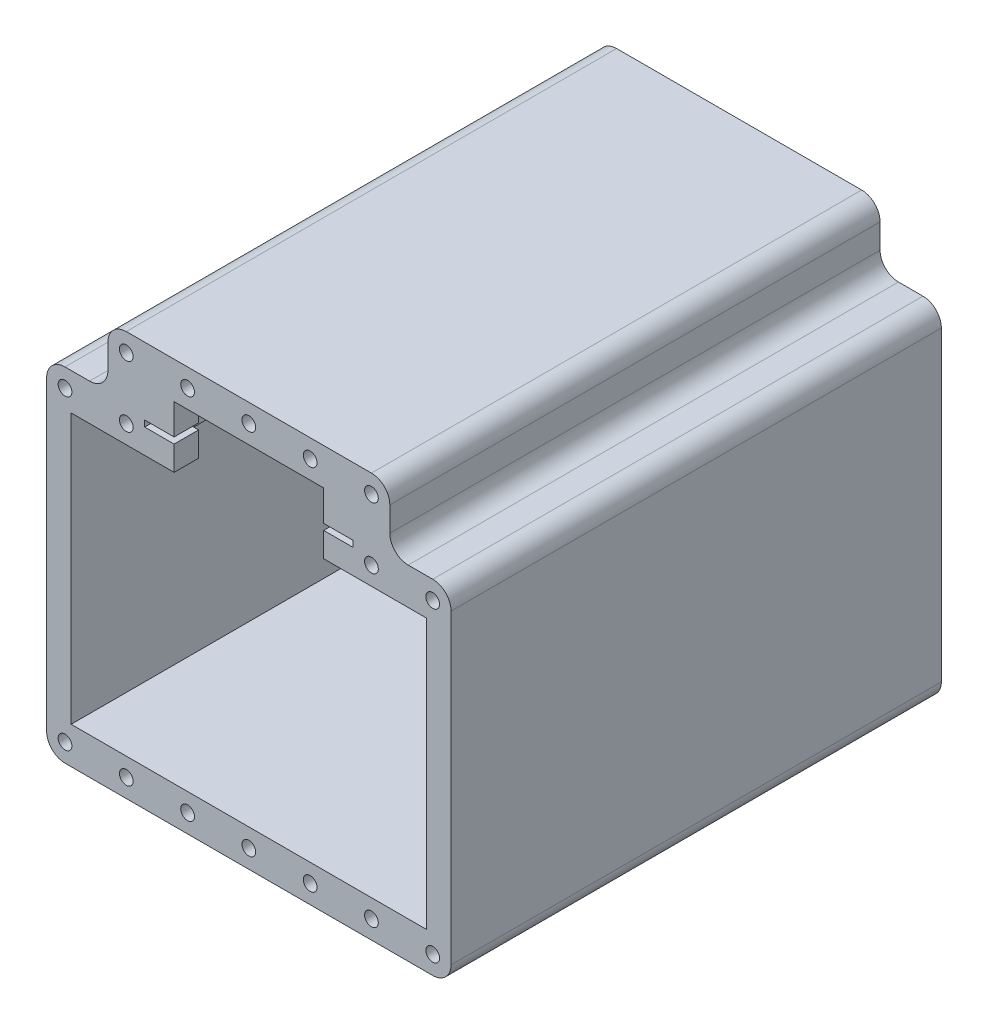
SolidWorks part; units mm, degrees
ref_plane "Front Plane" through (0, 0, 0) normal (0, 0, 1) x (1, 0, 0)
ref_plane "Top Plane" through (0, 0, 0) normal (0, 1, 0) x (1, 0, 0)
ref_plane "Right Plane" through (0, 0, 0) normal (1, 0, 0) x (0, 0, -1)
sketch "Sketch1" plane through (0, 0, 0) normal (0, 0, 1) x (1, 0, 0)
  line L0 (-57.5, 60) -> (-57.5, 50)
  line L1 (-75, -97.5) -> (75, -97.5)
  line L2 (-82.5, -90) -> (-82.5, 35)
  line L3 (-50, 67.5) -> (50, 67.5)
  line L4 (82.5, -90) -> (82.5, 35)
  line L5 (-82.5, 0) -> (82.5, 0) construction
  line L6 (-65, 42.5) -> (-75, 42.5)
  line L7 (57.5, 60) -> (57.5, 50)
  line L8 (65, 42.5) -> (75, 42.5)
  line L9 (0, -97.5) -> (0, 67.5) construction
  line L10 (-42.5, 52.5) -> (-42.5, 27.5)
  line L11 (-42.5, 27.5) -> (-72.5, 27.5)
  line L12 (-72.5, 27.5) -> (-72.5, -82.5)
  line L13 (-72.5, -82.5) -> (72.5, -82.5)
  line L14 (72.5, -82.5) -> (72.5, 27.5)
  line L15 (72.5, 27.5) -> (42.5, 27.5)
  line L16 (42.5, 27.5) -> (42.5, 52.5)
  line L17 (42.5, 52.5) -> (-42.5, 52.5)
  arc A0 (-82.5, 35) -> (-75, 42.5) centre (-75, 35) cw
  arc A1 (82.5, 35) -> (75, 42.5) centre (75, 35) ccw
  arc A2 (65, 42.5) -> (57.5, 50) centre (65, 50) cw
  arc A3 (57.5, 60) -> (50, 67.5) centre (50, 60) ccw
  arc A4 (-50, 67.5) -> (-57.5, 60) centre (-50, 60) ccw
  arc A5 (-65, 42.5) -> (-57.5, 50) centre (-65, 50) ccw
  arc A6 (-82.5, -90) -> (-75, -97.5) centre (-75, -90) ccw
  arc A7 (82.5, -90) -> (75, -97.5) centre (75, -90) cw
  point P0 (0, 0)
  dimension "D5" = 7.5
  dimension "D6" = 7.5
  dimension "D1" = 67.5
  dimension "D2" = 25
  dimension "D3" = 25
  dimension "D4" = 165
  dimension "D7" = 82.5
  dimension "D8" = 82.5
  dimension "D9" = 15
  dimension "D10" = 15
  dimension "D11" = 15
  dimension "D12" = 10
  dimension "D13" = 15
  dimension "D14" = 15
  dimension "D15" = 10
  dimension "D16" = 15
extrude "Boss-Extrude1" add sketch "Sketch1" against normal blind 200
sketch "Sketch2" plane through (0, 0, 0) normal (0, 0, 1) x (1, 0, 0)
  line L0 (-75, 35) -> (-50, 35) construction
  line L1 (-50, 35) -> (-50, 60) construction
  line L2 (-50, 60) -> (50, 60) construction
  line L3 (50, 60) -> (50, 35) construction
  line L4 (50, 35) -> (75, 35) construction
  line L5 (-75, -90) -> (75, -90) construction
  line L6 (50, 67.5) -> (-50, 67.5) construction
  line L7 (-57.5, 60) -> (-57.5, 50) construction
  line L8 (-65, 42.5) -> (-75, 42.5) construction
  line L9 (-82.5, 35) -> (-82.5, -90) construction
  line L10 (57.5, 50) -> (57.5, 60) construction
  line L11 (75, 42.5) -> (65, 42.5) construction
  line L12 (82.5, -90) -> (82.5, 35) construction
  line L13 (-75, -97.5) -> (75, -97.5) construction
  circle A0 centre (-75, 35) radius 2.8
  circle A1 centre (-50, 35) radius 2.8
  circle A2 centre (-50, 60) radius 2.8
  circle A3 centre (50, 60) radius 2.8
  circle A4 centre (25, 60) radius 2.8
  circle A5 centre (0, 60) radius 2.8
  circle A6 centre (-25, 60) radius 2.8
  circle A7 centre (50, 35) radius 2.8
  circle A8 centre (75, 35) radius 2.8
  circle A9 centre (-75, -90) radius 2.8
  circle A10 centre (-50, -90) radius 2.8
  circle A11 centre (-25, -90) radius 2.8
  circle A12 centre (0, -90) radius 2.8
  circle A13 centre (25, -90) radius 2.8
  circle A14 centre (50, -90) radius 2.8
  circle A15 centre (75, -90) radius 2.8
  dimension "D11" = 5.6
  dimension "D1" = 7.5
  dimension "D2" = 7.5
  dimension "D3" = 7.5
  dimension "D4" = 7.5
  dimension "D5" = 7.5
  dimension "D6" = 7.5
  dimension "D7" = 7.5
  dimension "D8" = 7.5
  dimension "D9" = 7.5
  dimension "D10" = 7.5
  dimension "D12" = 25
  dimension "D13" = 25
  dimension "D14" = 25
  dimension "D15" = 25
  dimension "D16" = 25
  dimension "D17" = 25
  dimension "D18" = 25
  dimension "D19" = 25
  dimension "D20" = 25
extrude "Cut-Extrude1" cut sketch "Sketch2" against normal through all both and the other way through all
sketch "Sketch3" plane through (0, 52.5, 0) normal (0, -1, 0) x (1, 0, 0)
  line L0 (-42.5, 0) -> (-42.5, -200) construction
  line L1 (42.5, 0) -> (42.5, -200) construction
  line L2 (-75, 0) -> (75, 0) construction
  line L3 (-75, -200) -> (75, -200) construction
  line L4 (42.5, -200) -> (42.5, 0) construction
  line L5 (-38, -23.6116) -> (-38, -172.8116) construction
  line L6 (-38, -172.8116) -> (38, -172.8116) construction
  line L7 (38, -172.8116) -> (38, -23.6116) construction
  line L8 (38, -23.6116) -> (-38, -23.6116) construction
  line L9 (-42.5, 0) -> (-42.5, -200)
  line L10 (-42.5, -200) -> (-17.5, -200)
  line L11 (-17.5, -200) -> (-17.5, 0)
  line L12 (-17.5, 0) -> (-42.5, 0)
  line L13 (42.5, 0) -> (17.5, 0)
  line L14 (17.5, 0) -> (17.5, -200)
  line L15 (17.5, -200) -> (42.5, -200)
  line L16 (42.5, -200) -> (42.5, 0)
  dimension "D1" = 76
  dimension "D2" = 149.2
  dimension "D3" = 25
  dimension "D4" = 25
  dimension "D5" = 4.5
extrude "Boss-Extrude2" add sketch "Sketch3" along normal up to surface (25 mm away) up to face at (-57.5, 27.5, -100)
sketch "Sketch4" plane through (-17.5, 0, 0) normal (1, 0, 0) x (0, 0, -1)
  line L0 (0, 52.5) -> (200, 52.5) construction
  line L1 (0, 27.5) -> (200, 27.5) construction
  line L2 (0, -90) -> (0, 35) construction
  line L3 (200, -90) -> (200, 35) construction
  line L4 (0, 27.5) -> (200, 27.5) construction
  line L5 (0, 40) -> (0, 37.5)
  line L6 (0, 27.5) -> (0, 52.5) construction
  line L7 (0, 37.5) -> (200, 37.5)
  line L8 (200, 27.5) -> (200, 52.5) construction
  line L9 (200, 37.5) -> (200, 40)
  line L10 (200, 40) -> (0, 40)
  line L11 (200, 40) -> (0, 40) construction
  dimension "D1" = 2.5
extrude "Cut-Extrude2" cut sketch "Sketch4" against normal blind 25
sketch "Sketch5" plane through (17.5, 0, 0) normal (-1, 0, 0) x (0, 0, 1)
  line L0 (-200, 27.5) -> (0, 27.5) construction
  line L1 (0, 52.5) -> (-200, 52.5) construction
  line L2 (-200, 40) -> (0, 40) construction
  line L3 (-200, 27.5) -> (-200, 52.5) construction
  line L4 (0, 27.5) -> (0, 52.5) construction
  line L5 (0, 40) -> (0, 37.5)
  line L6 (0, 37.5) -> (-200, 37.5)
  line L7 (-200, 37.5) -> (-200, 40)
  line L8 (-200, 40) -> (0, 40)
  dimension "D1" = 2.5
extrude "Cut-Extrude3" cut sketch "Sketch5" against normal blind 25
sketch "Sketch6" plane through (0, 52.5, 0) normal (0, -1, 0) x (1, 0, 0)
  line L0 (-30.5, 0) -> (-30.5, -10)
  line L1 (-17.5, 0) -> (-17.5, -200) construction
  line L2 (17.5, -200) -> (17.5, 0) construction
  line L3 (-42.5, -5) -> (42.5, -5) construction
  line L4 (17.5, 0) -> (-17.5, 0) construction
  line L20 (-17.5, 0) -> (-72.5, 0) construction
  line L30 (72.5, 0) -> (17.5, 0) construction
  line L75 (-30.5, -10) -> (-42.5, -10)
  line L76 (-42.5, -10) -> (-42.5, -60.8)
  line L80 (-42.5, -60.8) -> (-42.5, -140)
  line L81 (-42.5, -140) -> (-30.5, -140)
  line L102 (-30.5, -140) -> (42.5, -140)
  line L103 (42.5, -140) -> (42.5, -60.8)
  line L107 (42.5, -60.8) -> (42.5, -10)
  line L108 (42.5, -10) -> (30.5, -10)
  line L109 (30.5, -10) -> (30.5, 0)
  line L111 (30.5, 0) -> (42.5, 0)
  line L112 (42.5, 0) -> (42.5, 1)
  line L113 (42.5, 1) -> (-42.5, 1)
  line L114 (-42.5, 1) -> (-42.5, 0)
  line L115 (-42.5, 0) -> (-30.5, 0)
  dimension "D4" = 12
  dimension "D1" = 1
  dimension "D2" = 25
  dimension "D3" = 25
  dimension "D5" = 10
  dimension "D6" = 5
  dimension "D7" = 140
extrude "Cut-Extrude5" cut sketch "Sketch6" along normal up to surface (25 mm away) contours L115 L0 L75 L76 L80 L81 L102 L103 L107 L108 L109 L111 L112 L113 L114 up to face at (-45, 27.5, -100)
sketch "Sketch10" plane through (0, 27.5, 0) normal (0, -1, 0) x (1, 0, 0)
  line L0 (-42.5, -165) -> (-42.5, -200)
  line L1 (-17.5, -200) -> (-72.5, -200) construction
  line L2 (-42.5, -200) -> (42.5, -200)
  line L3 (42.5, -200) -> (42.5, -165)
  line L4 (42.5, -165) -> (-42.5, -165)
  line L5 (42.5, -10) -> (42.5, -140) construction
  line L6 (-42.5, -140) -> (-42.5, -10) construction
  line L7 (-17.5, -140) -> (-42.5, -140) construction
  dimension "D1" = 25
extrude "Cut-Extrude7" cut sketch "Sketch10" against normal up to surface (25 mm away) up to face at (0, 52.5, -83.3333)
sketch "Sketch11" plane through (0, 27.5, 0) normal (0, -1, 0) x (1, 0, 0)
  line L0 (-42.5, -165) -> (-42.5, -150)
  line L1 (-42.5, -150) -> (-17.5, -150)
  line L3 (-17.5, -150) -> (-17.5, -165)
  line L4 (-17.5, -165) -> (-42.5, -165)
  line L5 (17.5, -150) -> (17.5, -165)
  line L7 (17.5, -165) -> (42.5, -165)
  line L8 (42.5, -165) -> (42.5, -150)
  line L9 (42.5, -150) -> (17.5, -150)
  line L11 (30.5, 0) -> (-30.5, 0) construction
  dimension "D1" = 150
extrude "Boss-Extrude3" add sketch "Sketch11" against normal up to surface (25 mm away) up to face at (0, 52.5, -103.75)
sketch "Sketch12" plane through (0, 27.5, 0) normal (0, -1, 0) x (1, 0, 0)
  line L0 (-42.5, -140) -> (-42.5, -147.75)
  line L1 (-42.5, -147.75) -> (42.5, -147.75)
  line L2 (42.5, -147.75) -> (42.5, -140)
  line L3 (42.5, -140) -> (-42.5, -140)
  line L4 (42.5, -10) -> (42.5, -140) construction
  line L5 (-42.5, -150) -> (-17.5, -150) construction
  dimension "D1" = 2.25
extrude "Cut-Extrude8" cut sketch "Sketch12" against normal up to surface (25 mm away) up to face at (0, 52.5, -103.75)
